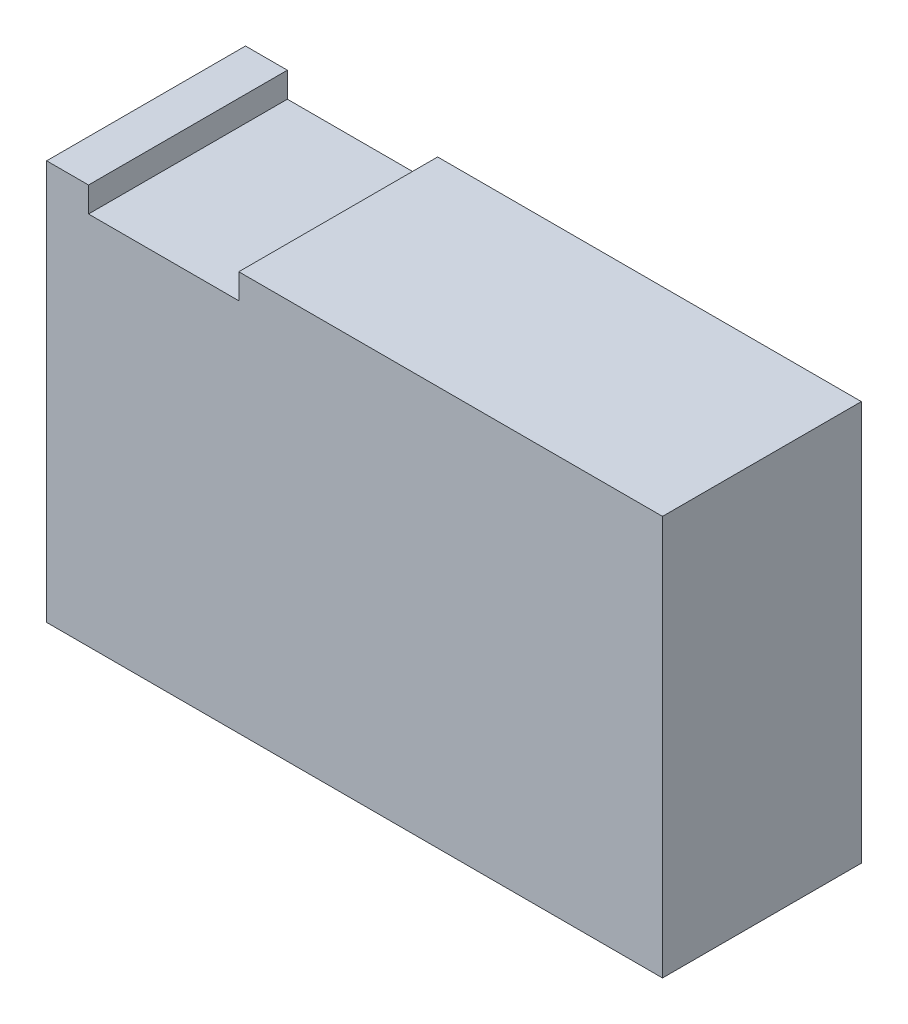
SolidWorks part; units mm, degrees
ref_plane "Спереди" through (0, 0, 0) normal (0, 0, 1) x (1, 0, 0)
ref_plane "Сверху" through (0, 0, 0) normal (0, 1, 0) x (1, 0, 0)
ref_plane "Справа" through (0, 0, 0) normal (1, 0, 0) x (0, 0, -1)
other "Configuration Table"
sketch "основание" plane through (0, 0, 0) normal (0, 1, 0) x (1, 0, 0)
  line L1 (-31.25, -10.09) -> (31.25, -10.09)
  line L2 (-31.25, -10.09) -> (-31.25, 10.09)
  line L3 (-31.25, 10.09) -> (31.25, 10.09)
  line L4 (31.25, -10.09) -> (31.25, 10.09)
  line L5 (-31.25, -10.09) -> (31.25, 10.09) construction
  line L6 (-31.25, 10.09) -> (31.25, -10.09) construction
  point P0 (0, 0)
  dimension "D1" = 20.18
  dimension "D2" = 62.5
extrude "Бобышка-Вытянуть1" add sketch "основание" along normal blind 40.57
sketch "Эскиз5" plane through (0, 40.57, 0) normal (0, 1, 0) x (1, 0, 0)
sketch "Эскиз6" plane through (0, 40.57, 0) normal (0, 1, 0) x (1, 0, 0)
  line L0 (31.25, 10.09) -> (-31.25, 10.09) construction
  line L1 (-27, 10.09) -> (-11.75, 10.09)
  line L2 (-27, 10.09) -> (-27, -10.09)
  line L3 (-27, -10.09) -> (-11.75, -10.09)
  line L4 (-11.75, 10.09) -> (-11.75, -10.09)
  line L5 (-31.25, -10.09) -> (31.25, -10.09) construction
  dimension "D1" = 15.25
  dimension "D2" = 4.25
extrude "Вырез-Вытянуть1" cut sketch "Эскиз6" against normal blind 2.55
